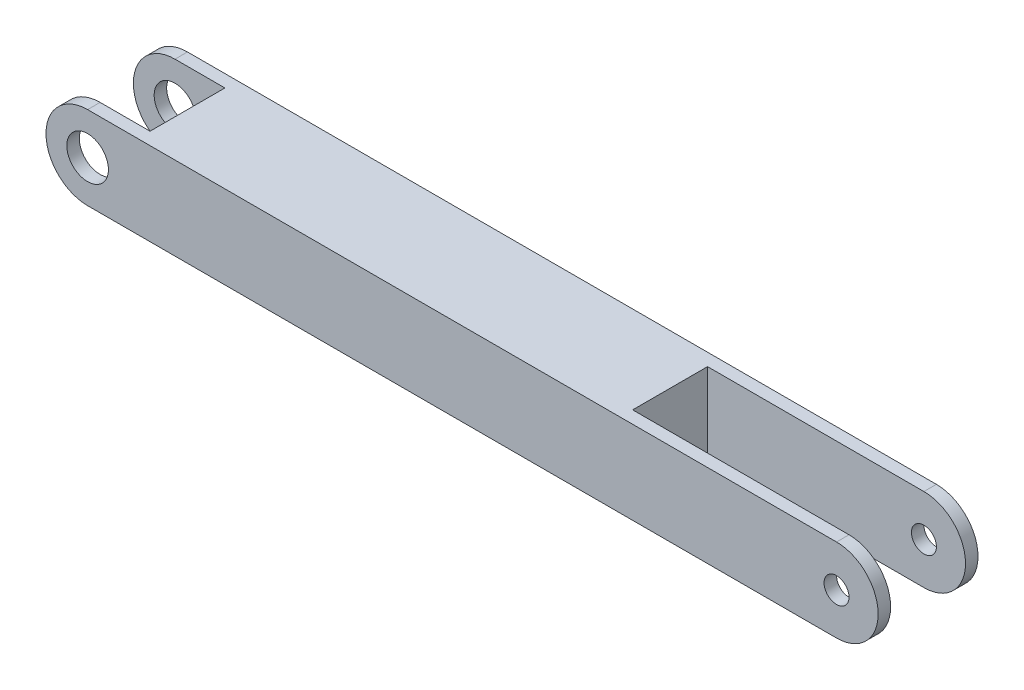
SolidWorks part; units mm, degrees
ref_plane "前视基准面" through (0, 0, 0) normal (0, 0, 1) x (1, 0, 0)
ref_plane "上视基准面" through (0, 0, 0) normal (0, 1, 0) x (1, 0, 0)
ref_plane "右视基准面" through (0, 0, 0) normal (1, 0, 0) x (0, 0, -1)
sketch "草图1" plane through (0, 0, 0) normal (0, 0, 1) x (1, 0, 0)
  line L0 (-50.916, 15.5344) -> (39.084, 15.5344)
  line L1 (-50.916, 5.5344) -> (39.084, 5.5344)
  arc A0 (-50.916, 15.5344) -> (-50.916, 5.5344) centre (-50.916, 10.5344) ccw
  arc A1 (39.084, 15.5344) -> (39.084, 5.5344) centre (39.084, 10.5344) cw
  dimension "D2" = 5
  dimension "D1" = 90
extrude "凸台-拉伸1" add sketch "草图1" along normal mid plane 12
sketch "草图2" plane through (0, 0, 6) normal (0, 0, 1) x (1, 0, 0)
  circle A0 centre (-50.916, 10.5344) radius 2.5
  circle A1 centre (39.084, 10.5344) radius 1.5
extrude "切除-拉伸1" cut sketch "草图2" against normal blind 12
sketch "草图3" plane through (0, 0, 0) normal (0, 0, 1) x (1, 0, 0)
  line L0 (39.084, 15.5344) -> (13.084, 15.5344)
  line L1 (39.084, 15.5344) -> (-50.916, 15.5344) construction
  line L2 (13.084, 15.5344) -> (13.084, 5.5344)
  line L3 (-50.916, 5.5344) -> (39.084, 5.5344) construction
  line L4 (13.084, 5.5344) -> (39.084, 5.5344)
  line L5 (-50.916, 15.5344) -> (-44.916, 15.5344)
  line L6 (-44.916, 15.5344) -> (-44.916, 5.5344)
  line L7 (-44.916, 5.5344) -> (-50.916, 5.5344)
  arc A0 (-50.916, 15.5344) -> (-50.916, 5.5344) centre (-50.916, 10.5344) ccw
  arc A1 (39.084, 15.5344) -> (39.084, 5.5344) centre (39.084, 10.5344) cw
extrude "切除-拉伸2" cut sketch "草图3" against normal mid plane 9
